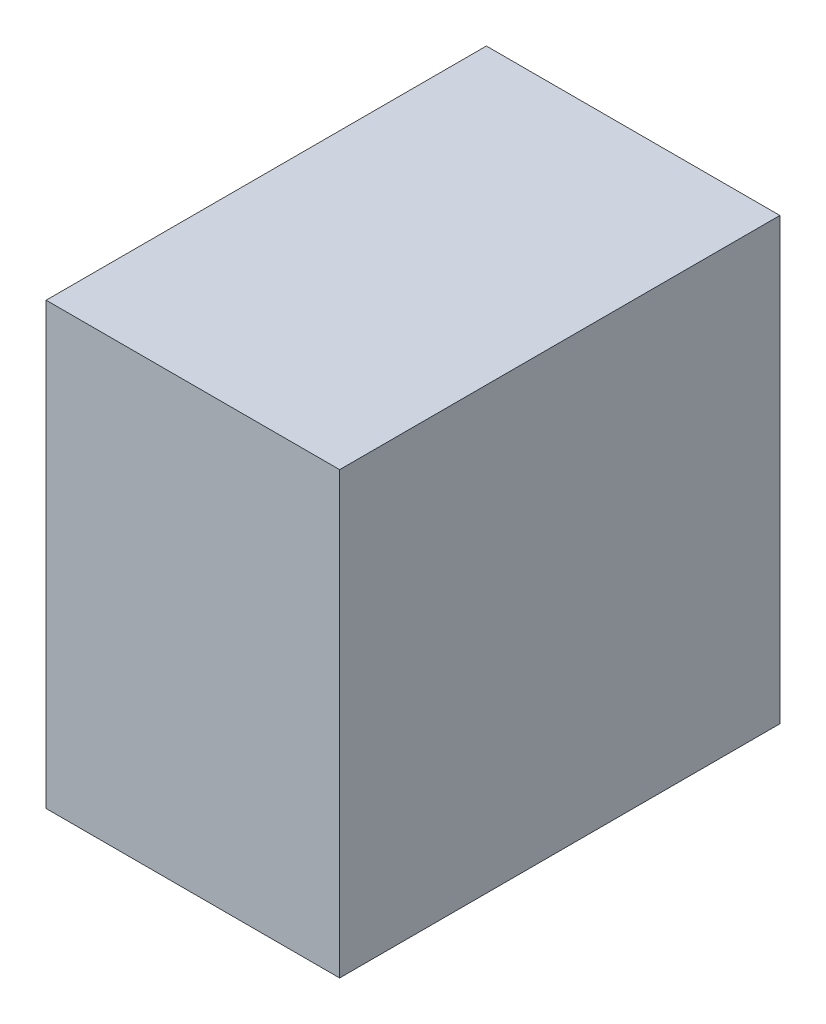
SolidWorks part; units mm, degrees
ref_plane "Alzado" through (0, 0, 0) normal (0, 0, 1) x (1, 0, 0)
ref_plane "Planta" through (0, 0, 0) normal (0, 1, 0) x (1, 0, 0)
ref_plane "Vista lateral" through (0, 0, 0) normal (1, 0, 0) x (0, 0, -1)
sketch "Sketch1" plane through (0, 0, 0) normal (0, 1, 0) x (1, 0, 0)
  line L1 (-20, -30) -> (20, -30)
  line L2 (-20, -30) -> (-20, 30)
  line L3 (-20, 30) -> (20, 30)
  line L4 (20, -30) -> (20, 30)
  line L5 (-20, -30) -> (20, 30) construction
  line L6 (-20, 30) -> (20, -30) construction
  point P0 (0, 0)
  dimension "D1" = 60
  dimension "D2" = 40
extrude "Boss-Extrude1" add sketch "Sketch1" along normal blind 60
